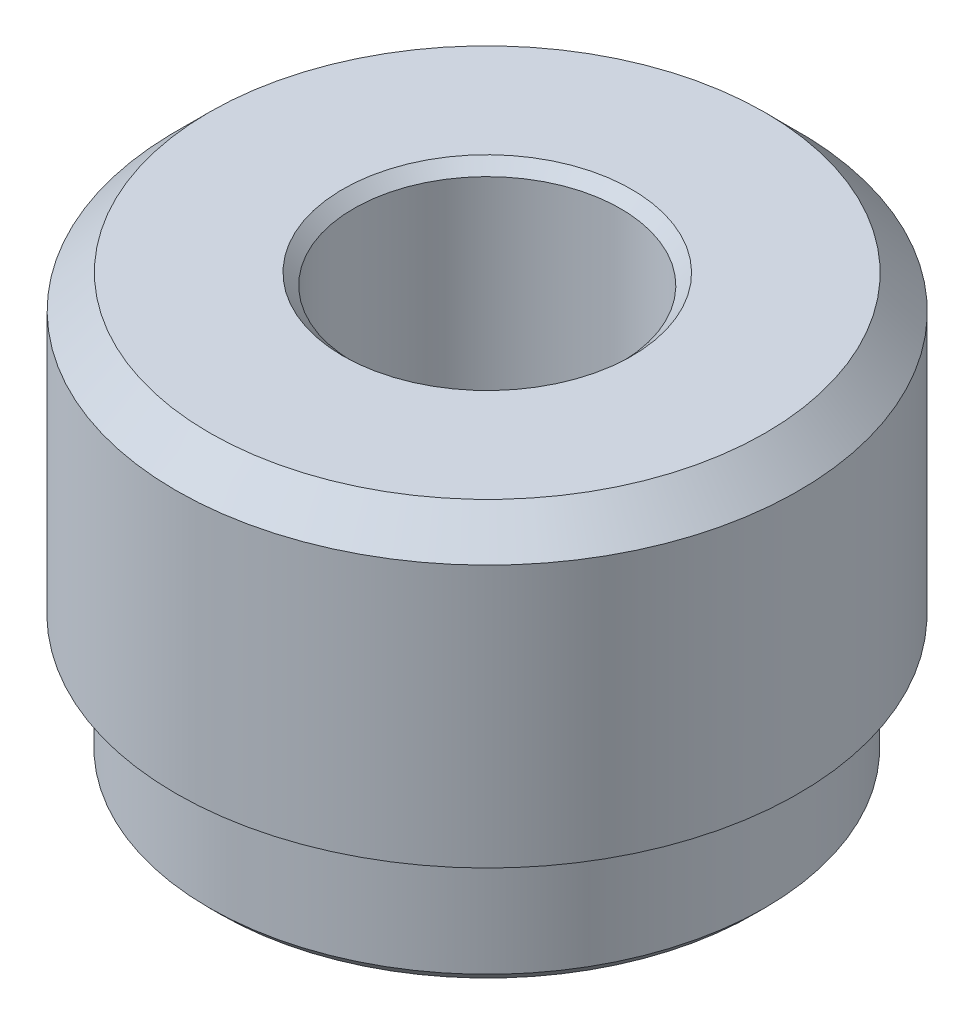
SolidWorks part; units mm, degrees
ref_plane "Plan1" through (0, 0, 0) normal (0, 0, 1) x (1, 0, 0)
ref_plane "Plan2" through (0, 0, 0) normal (0, 1, 0) x (1, 0, 0)
ref_plane "Plan3" through (0, 0, 0) normal (1, 0, 0) x (0, 0, -1)
ref_plane "Plan4" through (0, 0.5571, 739.9625) normal (0, -0.0008, -1) x (-1, 0, 0)
sketch "Esquisse1" plane through (0, 0.5571, 739.9625) normal (0, -0.0008, -1) x (-1, 0, 0)
  line L0 (-2199.4002, 598.9564) -> (-2198.9002, 599.4569)
  line L1 (-2198.9002, 599.4569) -> (-2198.9086, 617.4569)
  line L2 (-2198.9086, 617.4569) -> (-2199.4086, 617.9564)
  line L3 (-2199.4086, 617.9564) -> (-2205.4081, 617.9536)
  line L4 (-2205.4081, 617.9536) -> (-2206.9081, 616.4522)
  line L5 (-2206.9081, 616.4522) -> (-2206.9026, 604.6529)
  line L6 (-2206.9026, 604.6529) -> (-2205.4026, 604.6536)
  line L7 (-2205.4026, 604.6536) -> (-2205.4002, 599.4534)
  line L8 (-2205.4002, 599.4534) -> (-2204.9002, 598.9539)
  line L9 (-2204.9002, 598.9539) -> (-2199.4002, 598.9564)
  line L10 (-2192.9, 598.954) -> (-2192.9088, 617.965) construction
  dimension "D1" = 12
  dimension "D2" = 28
  dimension "D3" = 25
  dimension "D4" = 19
  dimension "D5" = 5.7
  dimension "D6" = 0.5
  dimension "D7" = 1.5
  dimension "D8" = 45
  dimension "D9" = 45
  dimension "D10" = 0.5
  dimension "D11" = 45
  dimension "D12" = 0.5
  dimension "D13" = 45
revolve "Base-Révolution" add sketch "Esquisse1" angle 360 about L10
